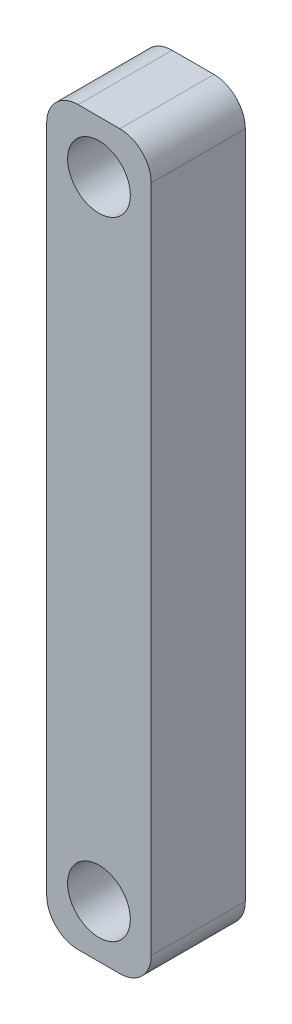
SolidWorks part; units mm, degrees
ref_plane "Front" through (0, 0, 0) normal (0, 0, 1) x (1, 0, 0)
ref_plane "Top" through (0, 0, 0) normal (0, 1, 0) x (1, 0, 0)
ref_plane "Right" through (0, 0, 0) normal (1, 0, 0) x (0, 0, -1)
sketch "Sketch1" plane through (0, 0, 0) normal (0, 0, 1) x (1, 0, 0)
  line L1 (-20.5497, 69.7557) -> (4.8503, 69.7557)
  line L2 (-20.5497, 69.7557) -> (-20.5497, -108.0443)
  line L3 (-20.5497, -108.0443) -> (4.8503, -108.0443)
  line L4 (4.8503, 69.7557) -> (4.8503, -108.0443)
  dimension "D1" = 25.4
  dimension "D2" = 177.8
extrude "Base-Extrude" add sketch "Sketch1" along normal blind 22.86
sketch "Sketch2" plane through (0, 0, 22.86) normal (0, 0, 1) x (1, 0, 0)
  line L0 (-7.8497, 69.7557) -> (-7.8497, -108.0443) construction
  line L1 (4.8503, 69.7557) -> (-20.5497, 69.7557) construction
  line L2 (-20.5497, -108.0443) -> (4.8503, -108.0443) construction
  circle A0 centre (-7.8497, -95.3443) radius 7.62
  circle A1 centre (-7.8497, 57.0557) radius 7.62
  dimension "D1" = 12.7
  dimension "D2" = 12.7
extrude "Cut-Extrude1" cut sketch "Sketch2" against normal blind 78.74
fillet "Fillet1" radius 7.62 4 edges at (-20.5497, 69.7557, 11.43) (4.8503, 69.7557, 11.43) (-20.5497, -108.0443, 11.43) (4.8503, -108.0443, 11.43)
